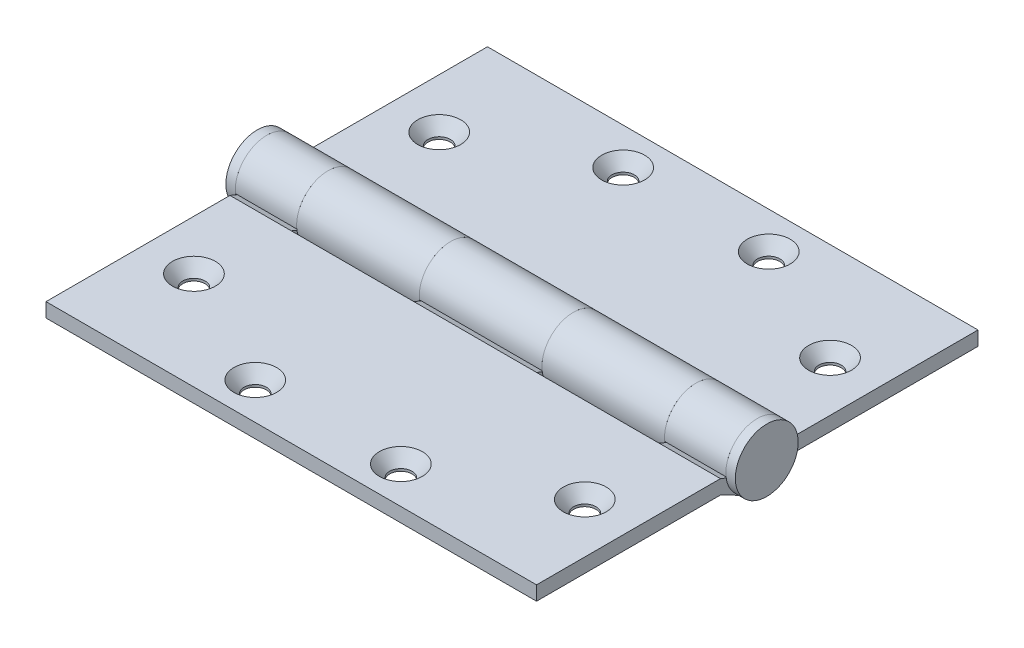
SolidWorks part; units mm, degrees
ref_plane "Front" through (0, 0, 0) normal (0, 0, 1) x (1, 0, 0)
ref_plane "Top" through (0, 0, 0) normal (0, 1, 0) x (1, 0, 0)
ref_plane "Right" through (0, 0, 0) normal (1, 0, 0) x (0, 0, -1)
sketch "Sketch1" plane through (0, 0, 0) normal (1, 0, 0) x (0, 0, -1)
  line L0 (-9.525, -4.2672) -> (-3.7042, -7.2438)
  line L1 (-57.15, -0.5842) -> (-9.525, -0.5842)
  line L2 (-9.525, -0.5842) -> (-1.5868, -3.8532)
  line L3 (-57.15, -4.2672) -> (-9.525, -4.2672)
  line L4 (-57.15, -0.5842) -> (-57.15, -4.2672)
  line L5 (-8.0858, -0.9022) -> (-2.8148, -3.0729)
  arc A0 (-1.5868, -3.8532) -> (-2.8148, -3.0729) centre (0, 0) ccw
  arc A1 (-3.7042, -7.2438) -> (-8.0858, -0.9022) centre (0, 0) ccw
  circle A2 centre (0, 0) radius 8.1359 construction
  circle A3 centre (0, 0) radius 4.1672 construction
  dimension "Th" = 3.683
  dimension "Open Width / 2" = 57.15
  dimension "Leaf End" = 47.625
  dimension "Leaf Top" = 0.5842
  dimension "D3" = 0.254
extrude "Left Leaf" add sketch "Sketch1" along normal mid plane 127
sketch "Sketch2" plane through (0, 0, 0) normal (0, 1, 0) x (1, 0, 0)
  line L0 (47.625, -9.525) -> (47.625, 8.1359)
  line L2 (0, 8.1359) -> (0, -57.15) construction
  line L3 (63.5, 8.1359) -> (-63.5, 8.1359) construction
  line L4 (47.625, 8.1359) -> (15.875, 8.1359)
  line L5 (15.875, 8.1359) -> (15.875, -9.525)
  line L7 (63.5, -57.15) -> (-63.5, -57.15) construction
  line L8 (-47.625, -9.525) -> (-47.625, 8.1359)
  line L9 (15.875, -9.525) -> (47.625, -9.525)
  line L10 (-15.875, -9.525) -> (-47.625, -9.525)
  line L11 (-15.875, 8.1359) -> (-15.875, -9.525)
  line L12 (-47.625, 8.1359) -> (-15.875, 8.1359)
  line L14 (-15.875, 8.1359) -> (15.875, 8.1359) construction
  dimension "Knuckle Lg" = 31.75
extrude "Cut-Extrude1" cut sketch "Sketch2" against normal through all and the other way through all
sketch "Sketch3" plane through (47.625, 0, 0) normal (1, 0, 0) x (0, 0, -1)
  line L0 (0, 8.1359) -> (0, -4.2672) construction
  line L1 (-57.15, -4.2672) -> (-9.525, -4.2672) construction
  line L2 (9.525, -4.2672) -> (3.7042, -7.2438)
  line L3 (9.525, -0.5842) -> (1.5868, -3.8532)
  line L4 (2.8148, -3.0729) -> (8.0858, -0.9022)
  line L6 (9.525, -4.2672) -> (57.15, -4.2672)
  line L7 (57.15, -4.2672) -> (57.15, -0.5842)
  line L9 (-57.15, -0.5842) -> (-57.15, -4.2672) construction
  line L10 (57.15, -0.5842) -> (9.525, -0.5842)
  arc A0 (-3.7042, -7.2438) -> (-8.0858, -0.9022) centre (0, 0) ccw construction
  circle A5 centre (0, 0) radius 8.1359 construction
  arc A6 (3.7042, -7.2438) -> (8.0858, -0.9022) centre (0, 0) cw
  arc A7 (-1.5868, -3.8532) -> (-2.8148, -3.0729) centre (0, 0) ccw construction
  arc A8 (2.8148, -3.0729) -> (1.5868, -3.8532) centre (0, 0) ccw
extrude "Right Leaf" add sketch "Sketch3" against normal up to surface (31.75 mm away) separate body up to face at (15.875, -0.7076, 3.0362)
mirror "Mirror1" about plane through (0, 0, 0) normal (1, 0, 0) of bodies 110
sketch "Sketch4" plane through (0, 0, 0) normal (-1, 0, 0) x (0, 0, 1)
  line L0 (-9.525, -0.5842) -> (-9.525, -4.2672)
  line L1 (-57.15, -0.5842) -> (-9.525, -0.5842)
  line L2 (0, 8.1359) -> (0, -4.2672) construction
  line L6 (-9.525, -4.2672) -> (-57.15, -4.2672)
  line L8 (-57.15, -4.2672) -> (-57.15, -0.5842)
extrude "Extrude3" add sketch "Sketch4" along normal up to surface and the other way up to surface
combine bodies "Combine1" operation type add bodies to combine 125 110 111
sketch "Sketch6" plane through (0, 0, 0) normal (0, 1, 0) x (1, 0, 0)
  line L0 (24.5662, 0) -> (-23.3403, 0) construction
  line L1 (63.5, -8.1359) -> (63.5, 8.1359) construction
  line L2 (-63.5, 0) -> (63.5, 0)
  line L3 (-63.5, 0) -> (-63.5, -4.1672)
  line L4 (-63.5, -4.1672) -> (63.5, -4.1672)
  line L5 (63.5, 0) -> (63.5, -4.1672)
  line L6 (-63.5, -4.1672) -> (-63.5, 4.1672) construction
  dimension "D1" = 8.3344
revolve "Pin" add sketch "Sketch6" angle 360 about L0
sketch "Sketch7" plane through (0, 0, 0) normal (0, 1, 0) x (1, 0, 0)
  line L0 (24.5662, 0) -> (-23.3403, 0) construction
  line L1 (0, 57.15) -> (0, -57.15) construction
  line L2 (24.5662, 0) -> (-23.3403, 0) construction
  line L3 (-65.9553, 0) -> (-65.9553, -8.1359)
  line L4 (-65.9553, 0) -> (-63.5, 0)
  line L5 (-63.5, 0) -> (-63.5, -8.1359)
  line L6 (-63.5, 57.15) -> (63.5, 57.15) construction
  line L7 (-65.9553, -8.1359) -> (-63.5, -8.1359)
  line L8 (65.9553, 0) -> (65.9553, -8.1359)
  line L9 (63.5, 0) -> (63.5, -8.1359)
  line L10 (65.9553, 0) -> (63.5, 0)
  line L11 (65.9553, -8.1359) -> (63.5, -8.1359)
  dimension "D1" = 2.4553
revolve "Spun Pin" add sketch "Sketch7" angle 360 about L0
sketch "Sketch8" plane through (0, -0.5842, 0) normal (0, 1, 0) x (-1, 0, 0)
  line L3 (63.5, 0) -> (-63.5, 0) construction
  line L4 (0, -57.15) -> (0, 57.15) construction
  line L5 (63.5, -57.15) -> (-63.5, -57.15) construction
  line L6 (0, 57.15) -> (0, 9.525) construction
  line L7 (-63.5, 57.15) -> (63.5, 57.15) construction
  point P3 (18.8468, -47.625)
  point P4 (-18.8468, -47.625)
  point P8 (-18.8468, 47.625)
  point P9 (18.8468, 47.625)
  point P12 (50.5968, -31.75)
  point P23 (-50.5968, -31.75)
  point P24 (-50.5968, 31.75)
  point P25 (50.5968, 31.75)
  dimension "Hole Dist" = 37.6936
  dimension "Hole Dist2" = 9.525
  dimension "Hole Dist3" = 31.75
  dimension "Hole Dist4" = 25.4
hole_wizard "CSK for #12 Flat Head Machine Screw1" positions "3DSketch1" profile "Sketch9" countersink size "#12" standard "Ansi Inch" end condition through all
sketch3d "3DSketch1"
  point P30 (-18.8468, -0.5842, 47.625)
  point P33 (-18.8468, -0.5842, -47.625)
  point P36 (18.8468, -0.5842, -47.625)
  point P39 (18.8468, -0.5842, 47.625)
  point P43 (-50.5968, -0.5842, -31.75)
  point P46 (50.5968, -0.5842, -31.75)
  point P49 (-50.5968, -0.5842, 31.75)
  point P52 (50.5968, -0.5842, 31.75)
sketch "Sketch9" plane through (-18.8468, -0.5842, 47.625) normal (1, 0, 0) x (0, 0, 1)
  line L0 (0, 0) -> (0, 7.5517)
  line L1 (0, 7.5517) -> (2.8956, 7.5517)
  line L2 (2.8956, 7.5517) -> (2.8956, 3.068)
  line L3 (2.8956, 3.068) -> (5.5626, 0)
  line L5 (5.5626, 0) -> (0, 0)
  line L6 (-2.8956, 3.068) -> (-5.5626, 0) construction
  line L11 (0, -6.35) -> (0, 107.95) construction
  dimension "Thru Hole Dia." = 5.7912
  dimension "Thru Hole Depth" = 7.5517
  dimension "Near C'Sink Dia." = 11.1252
  dimension "Near C'Sink Angle" = 82
equation "\"D1@Sketch7\"=\"Th@Sketch1\"/1.5"
equation "\"D1@Sketch6\" = \"Pin Dia.@Sketch1\""
